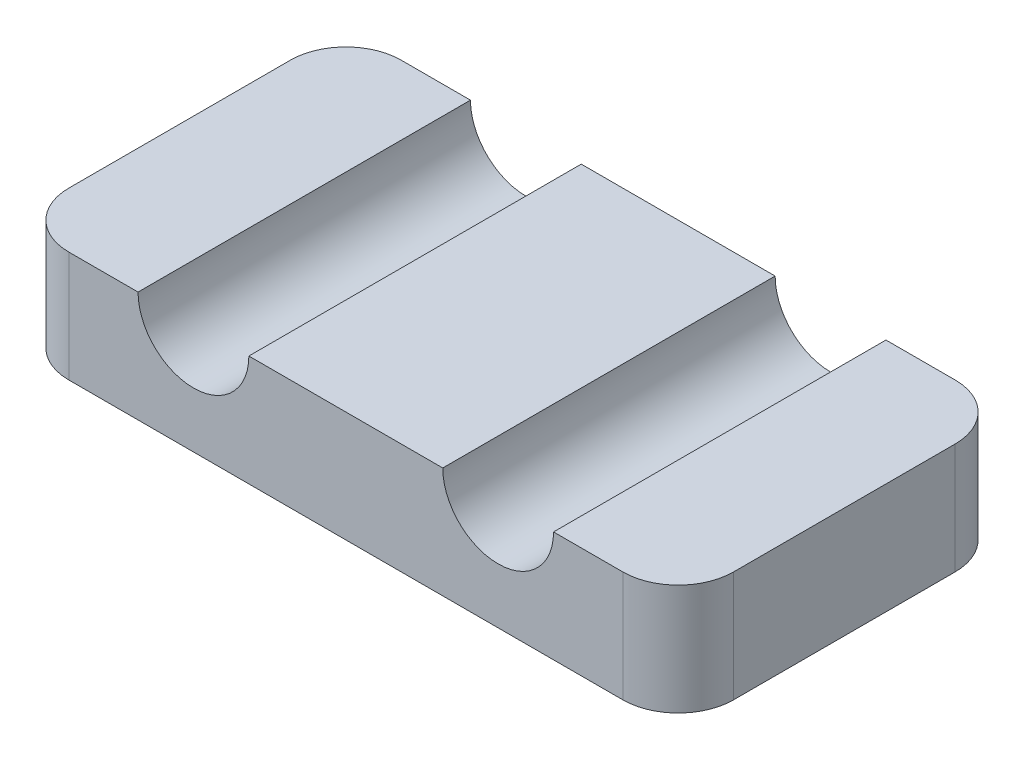
SolidWorks part; units mm, degrees
ref_plane "Front Plane" through (0, 0, 0) normal (0, 0, 1) x (1, 0, 0)
ref_plane "Top Plane" through (0, 0, 0) normal (0, 1, 0) x (1, 0, 0)
ref_plane "Right Plane" through (0, 0, 0) normal (1, 0, 0) x (0, 0, -1)
sketch "Sketch1" plane through (0, 0, 0) normal (0, 0, 1) x (1, 0, 0)
  line L1 (-152.4, -25.4) -> (152.4, -25.4)
  line L2 (-152.4, -25.4) -> (-152.4, 25.4)
  line L3 (-152.4, 25.4) -> (152.4, 25.4)
  line L4 (152.4, -25.4) -> (152.4, 25.4)
  line L5 (-152.4, -25.4) -> (152.4, 25.4) construction
  line L6 (-152.4, 25.4) -> (152.4, -25.4) construction
  circle A1 centre (-69.85, 25.4) radius 25.4
  circle A3 centre (69.85, 25.4) radius 25.4
  point P0 (0, 0)
  point P6 (0, 0)
  dimension "D3" = 50.8
  dimension "D4" = 50.8
  dimension "D1" = 304.8
  dimension "D2" = 50.8
  dimension "D5" = 69.85
  dimension "D6" = 69.85
extrude "Boss-Extrude1" add sketch "Sketch1" along normal mid plane 152.4 contours A3 L3 A1 L2 L1 L4
fillet "Fillet1" radius 25.4 4 edges at (152.4, 0, 76.2) (152.4, 0, -76.2) (-152.4, 0, -76.2) (-152.4, 0, 76.2)
sketch "Sketch2" plane through (0, 25.4, 0) normal (0, 1, 0) x (1, 0, 0)
  circle A0 centre (-127, 50.8) radius 7.747
  circle A1 centre (-127, -50.8) radius 7.747
  circle A2 centre (127, 50.8) radius 7.747
  circle A3 centre (127, -50.8) radius 7.747
  dimension "D1" = 15.494
  dimension "D6" = 15.494
  dimension "D2" = 254
  dimension "D3" = 101.6
  dimension "D4" = 101.6
  dimension "D5" = 254
